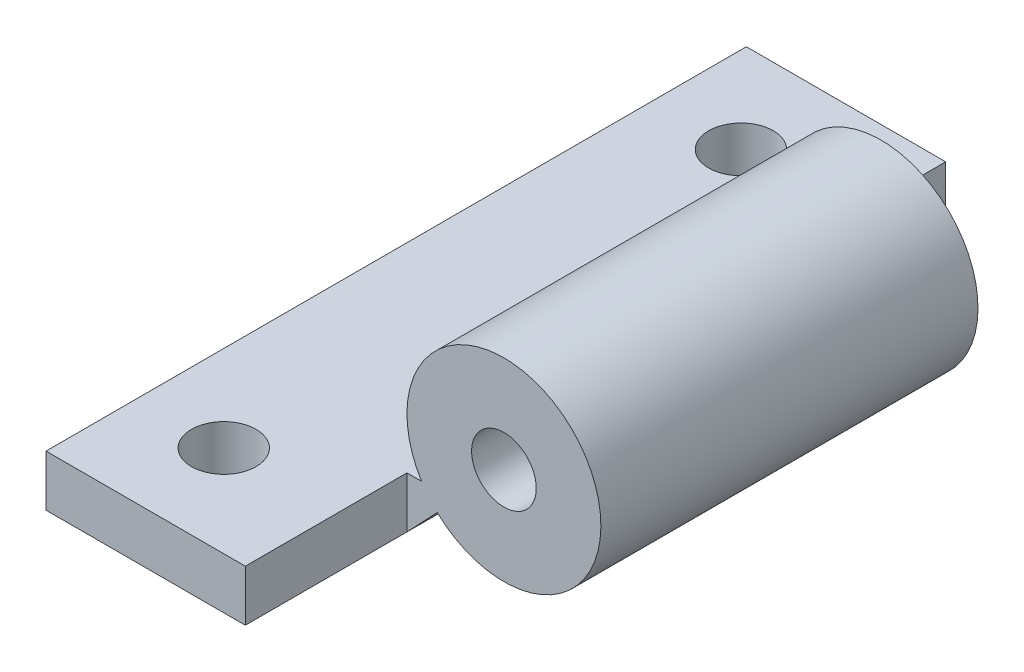
SolidWorks part; units mm, degrees
ref_plane "前视基准面" through (0, 0, 0) normal (0, 0, 1) x (1, 0, 0)
ref_plane "上视基准面" through (0, 0, 0) normal (0, 1, 0) x (1, 0, 0)
ref_plane "右视基准面" through (0, 0, 0) normal (1, 0, 0) x (0, 0, -1)
sketch "草图1" plane through (0, 0, 0) normal (0, 0, 1) x (1, 0, 0)
  line L2 (-27.5, 4.75) -> (-27.5, 0)
  line L3 (-27.5, 0) -> (-9, 0)
  line L4 (-9, 0) -> (-6.1897, 2.9664)
  line L5 (-7.6444, 4.75) -> (-27.5, 4.75)
  arc A0 (-6.1897, 2.9664) -> (-7.6444, 4.75) centre (0, 9.5) ccw
extrude "凸台-拉伸1" add sketch "草图1" along normal blind 65
sketch "草图2" plane through (0, 4.75, 0) normal (0, 1, 0) x (1, 0, 0)
  line L0 (-27.5, 0) -> (-19.5, 0)
  line L1 (-7.6444, 0) -> (-27.5, 0) construction
  circle A0 centre (-19.5, -8.5) radius 3
  circle A1 centre (-19.5, -56.5) radius 3
extrude "切除-拉伸1" cut sketch "草图2" against normal blind 65 contours A0 | A1
sketch "草图3" plane through (0, 4.75, 0) normal (0, 1, 0) x (1, 0, 0)
  line L0 (-9, 0) -> (-9, -15)
  line L1 (-9, 0) -> (-9, -65) construction
  line L2 (-9, -15) -> (9, -15)
  line L3 (9, -65) -> (9, 0) construction
  line L4 (9, -15) -> (9, 0)
  line L5 (9, 0) -> (-9, 0)
  line L6 (-9, -65) -> (-9, -50)
  line L7 (-9, -50) -> (9, -50)
  line L8 (9, -50) -> (9, -65)
  line L9 (9, -65) -> (-9, -65)
extrude "切除-拉伸2" cut sketch "草图3" against normal mid plane 50
sketch "草图4" plane through (0, 0, 50) normal (0, 0, 1) x (1, 0, 0)
  circle A0 centre (0, 9.5) radius 3
extrude "切除-拉伸3" cut sketch "草图4" against normal blind 50
